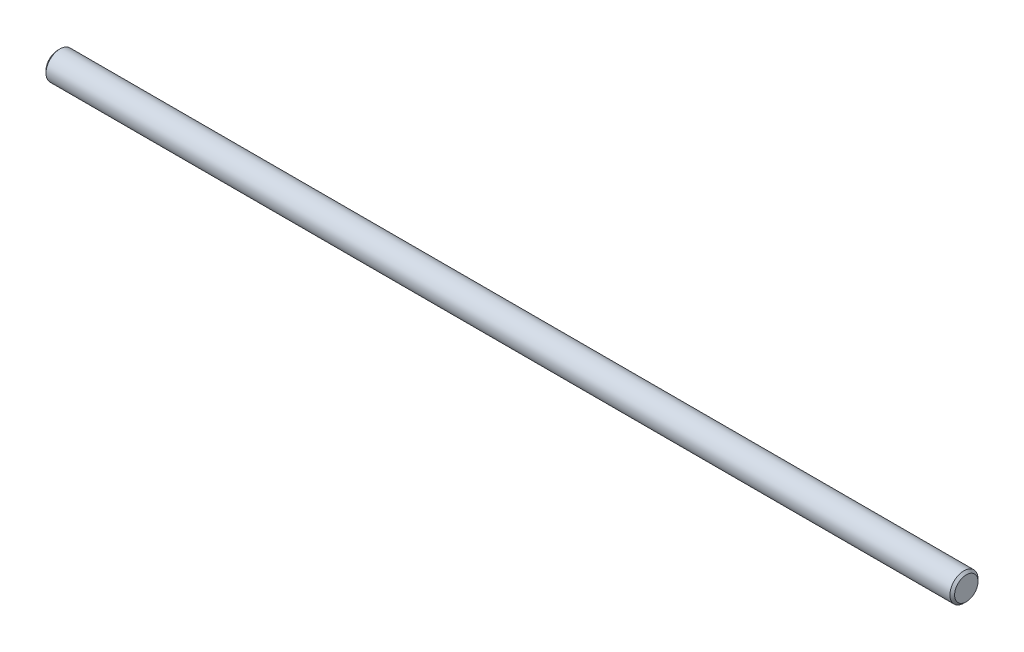
SolidWorks part; units mm, degrees
material "Chrome Stainless Steel"
ref_plane "Front Plane" through (0, 0, 0) normal (0, 0, 1) x (1, 0, 0)
ref_plane "Top Plane" through (0, 0, 0) normal (0, 1, 0) x (1, 0, 0)
ref_plane "Right Plane" through (0, 0, 0) normal (1, 0, 0) x (0, 0, -1)
sketch "Sketch1" plane through (0, 0, 0) normal (1, 0, 0) x (0, 0, -1)
  circle A0 centre (0, 0) radius 6
  dimension "D1" = 12
extrude "Boss-Extrude1" add sketch "Sketch1" along normal blind 388
chamfer "Chamfer1" distance 1 angle 45 2 edges at (388, 0, -6) (0, 0, -6)
